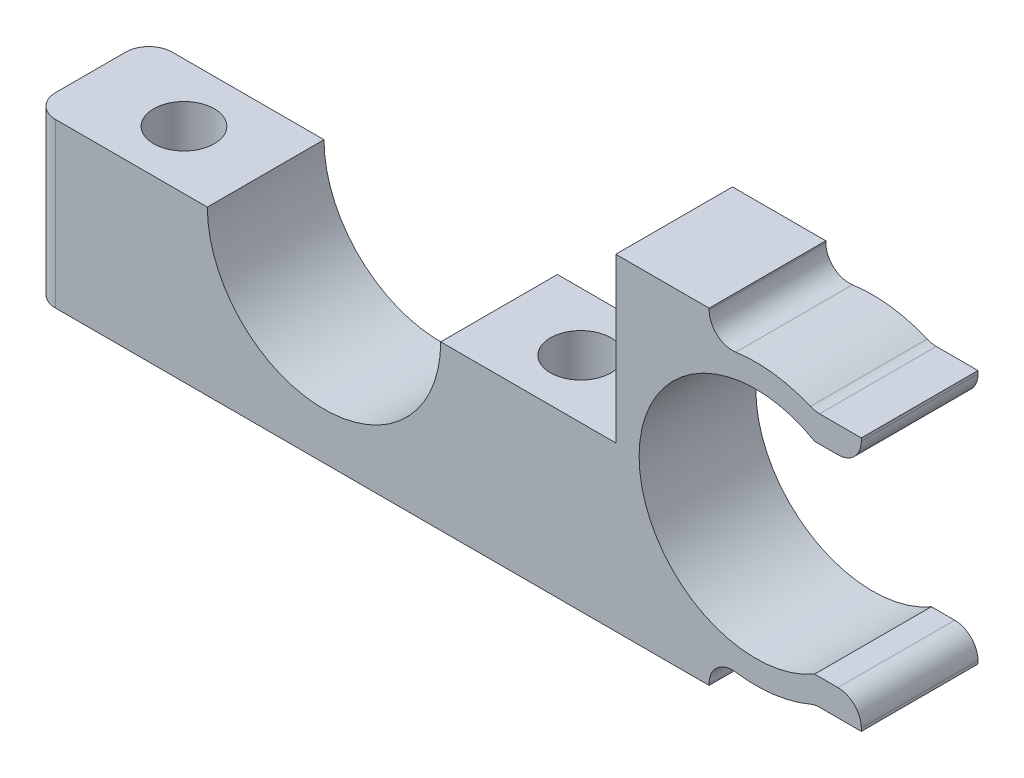
SolidWorks part; units mm, degrees
ref_plane "Front Plane" through (0, 0, 0) normal (0, 0, 1) x (1, 0, 0)
ref_plane "Top Plane" through (0, 0, 0) normal (0, 1, 0) x (1, 0, 0)
ref_plane "Right Plane" through (0, 0, 0) normal (1, 0, 0) x (0, 0, -1)
sketch "Sketch1" plane through (0, 0, 0) normal (0, 0, 1) x (1, 0, 0)
  line L0 (10, 0) -> (25, 0)
  line L1 (25, 0) -> (37, 0) construction
  line L2 (33, -11.3137) -> (33, -14)
  line L3 (25, 14) -> (33, 14)
  line L4 (25, 14) -> (25, 0)
  line L5 (-25, 0) -> (-10, 0)
  line L6 (-25, 0) -> (-25, -14)
  line L7 (-25, -14) -> (25, -14)
  line L8 (25, 0) -> (49, 0) construction
  line L9 (25, -14) -> (33, -14)
  line L10 (33, 14) -> (33, 11.3137)
  line L11 (42.0406, -10.89) -> (42.0406, 10.89) construction
  line L13 (42.0406, 10.89) -> (46.0406, 10.89)
  line L14 (42.0406, 10.89) -> (42.0406, 8.6367) construction
  line L15 (42.0406, 8.6367) -> (46.0406, 8.6367)
  line L16 (46.0406, 10.89) -> (46.0406, 8.6367)
  line L17 (42.0406, -8.6367) -> (46.0406, -8.6367)
  line L18 (42.0406, -8.6367) -> (42.0406, -10.89) construction
  line L19 (42.0406, -10.89) -> (46.0406, -10.89)
  line L20 (46.0406, -8.6367) -> (46.0406, -10.89)
  arc A0 (-10, 0) -> (10, 0) centre (0, 0) ccw
  arc A1 (42.0406, 8.6367) -> (42.0406, -8.6367) centre (37, 0) ccw
  arc A2 (33, -11.3137) -> (42.0406, -10.89) centre (37, 0) ccw
  arc A3 (42.0406, 10.89) -> (33, 11.3137) centre (37, 0) ccw
  dimension "D3" = 20
  dimension "D5" = 20
  dimension "D6" = 24
  dimension "D1" = 12
  dimension "D2" = 50
  dimension "D4" = 14
  dimension "D7" = 28
  dimension "D8" = 8
  dimension "D9" = 4
extrude "Boss-Extrude1" add sketch "Sketch1" along normal blind 10
fillet "Fillet1" radius 2 8 edges at (46.0406, -8.6367, 5) (46.0406, 8.6367, 5) (-25, -7, 0) (-25, -7, 10) (42.0406, 10.89, 5) (42.0406, -10.89, 5) (33, -11.3137, 5) (33, 11.3137, 5)
sketch "Sketch4" plane through (0, 0, 0) normal (0, 1, 0) x (1, 0, 0)
  line L0 (-17, -5) -> (17, -5) construction
  line L1 (0, 0) -> (0, -5) construction
  circle A0 centre (-17, -5) radius 2.6
  circle A1 centre (17, -5) radius 2.6
  point P7 (0, -5)
  dimension "D2" = 5.2
  dimension "D1" = 34
  dimension "D3" = 5
extrude "Cut-Extrude2" cut sketch "Sketch4" against normal through all
